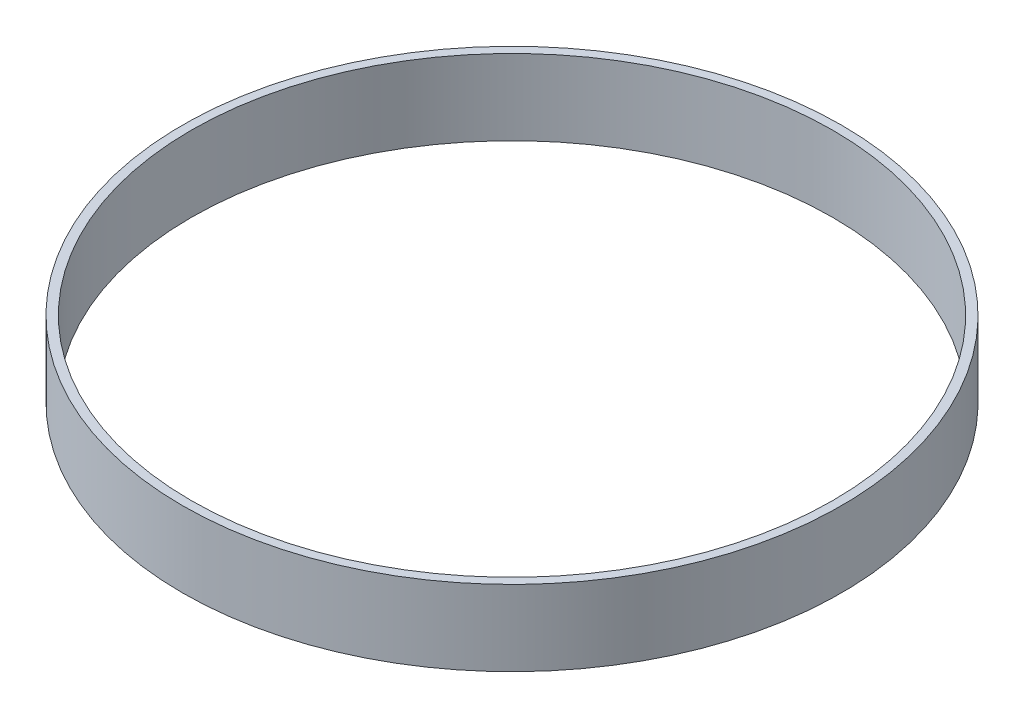
SolidWorks part; units mm, degrees
material "6061-T6 (SS)"
ref_plane "Piano frontale" through (0, 0, 0) normal (0, 0, 1) x (1, 0, 0)
ref_plane "Piano superiore" through (0, 0, 0) normal (0, 1, 0) x (1, 0, 0)
ref_plane "Piano destro" through (0, 0, 0) normal (1, 0, 0) x (0, 0, -1)
sketch "Schizzo1" plane through (0, 0, 0) normal (0, 0, 1) x (1, 0, 0)
  line L0 (-73, 0) -> (-75, 0)
  line L1 (-75, 0) -> (-75, 17.2)
  line L2 (-75, 17.2) -> (-73, 17.2)
  line L3 (-73, 17.2) -> (-73, 0)
  line L4 (0, 0) -> (0, 80.9593) construction
  dimension "D1" = 146
  dimension "D2" = 150
  dimension "D3" = 17.2
revolve "Rivoluzione1" add sketch "Schizzo1" angle 360 about L4
